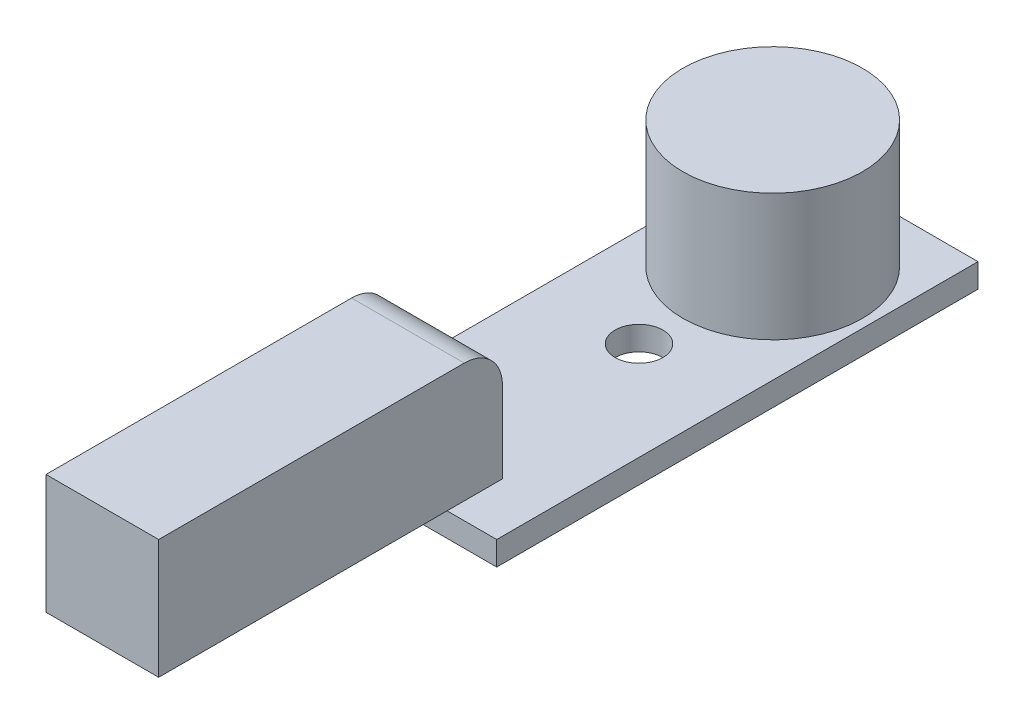
SolidWorks part; units mm, degrees
ref_plane "Front Plane" through (0, 0, 0) normal (0, 0, 1) x (1, 0, 0)
ref_plane "Top Plane" through (0, 0, 0) normal (0, 1, 0) x (1, 0, 0)
ref_plane "Right Plane" through (0, 0, 0) normal (1, 0, 0) x (0, 0, -1)
sketch "Sketch1" plane through (0, 0, 0) normal (0, 1, 0) x (1, 0, 0)
  line L1 (-6.5405, -16.002) -> (6.5405, -16.002)
  line L2 (-6.5405, -16.002) -> (-6.5405, 16.002)
  line L3 (-6.5405, 16.002) -> (6.5405, 16.002)
  line L4 (6.5405, -16.002) -> (6.5405, 16.002)
  line L5 (-6.5405, -16.002) -> (6.5405, 16.002) construction
  line L6 (-6.5405, 16.002) -> (6.5405, -16.002) construction
  circle A0 centre (0, 0) radius 1.5875
  circle A1 centre (0, 8.89) radius 5.969
  point P0 (0, 0)
  point P10 (0, 9.4594)
  dimension "D3" = 3.175
  dimension "D4" = 11.938
  dimension "D1" = 13.081
  dimension "D2" = 32.004
  dimension "D5" = 7.112
extrude "Boss-Extrude1" add sketch "Sketch1" along normal blind 1.5875 contours A1 | L1 L4 L3 L2 A1 A0
sketch "Sketch2" plane through (0, 1.5875, 0) normal (0, 1, 0) x (1, 0, 0)
  circle A0 centre (0, 8.89) radius 5.969 construction
  circle A1 centre (0, 8.89) radius 5.969
extrude "Boss-Extrude2" add sketch "Sketch2" along normal blind 8.4455
sketch "Sketch3" plane through (0, 1.5875, 0) normal (0, 1, 0) x (1, 0, 0)
  line L0 (-6.5405, -16.002) -> (-6.5405, 16.002) construction
  line L1 (-4.2545, -12.319) -> (3.2385, -12.319)
  line L2 (-4.2545, -12.319) -> (-4.2545, -35.179)
  line L3 (-4.2545, -35.179) -> (3.2385, -35.179)
  line L4 (3.2385, -12.319) -> (3.2385, -35.179)
  line L5 (6.5405, -16.002) -> (6.5405, 16.002) construction
  line L6 (-6.5405, -16.002) -> (6.5405, -16.002) construction
  dimension "D1" = 2.286
  dimension "D2" = 3.302
  dimension "D3" = 22.86
  dimension "D4" = 3.683
extrude "Boss-Extrude3" add sketch "Sketch3" along normal blind 7.9375
fillet "Fillet1" radius 2.54 1 edges at (-0.508, 9.525, 12.319)
